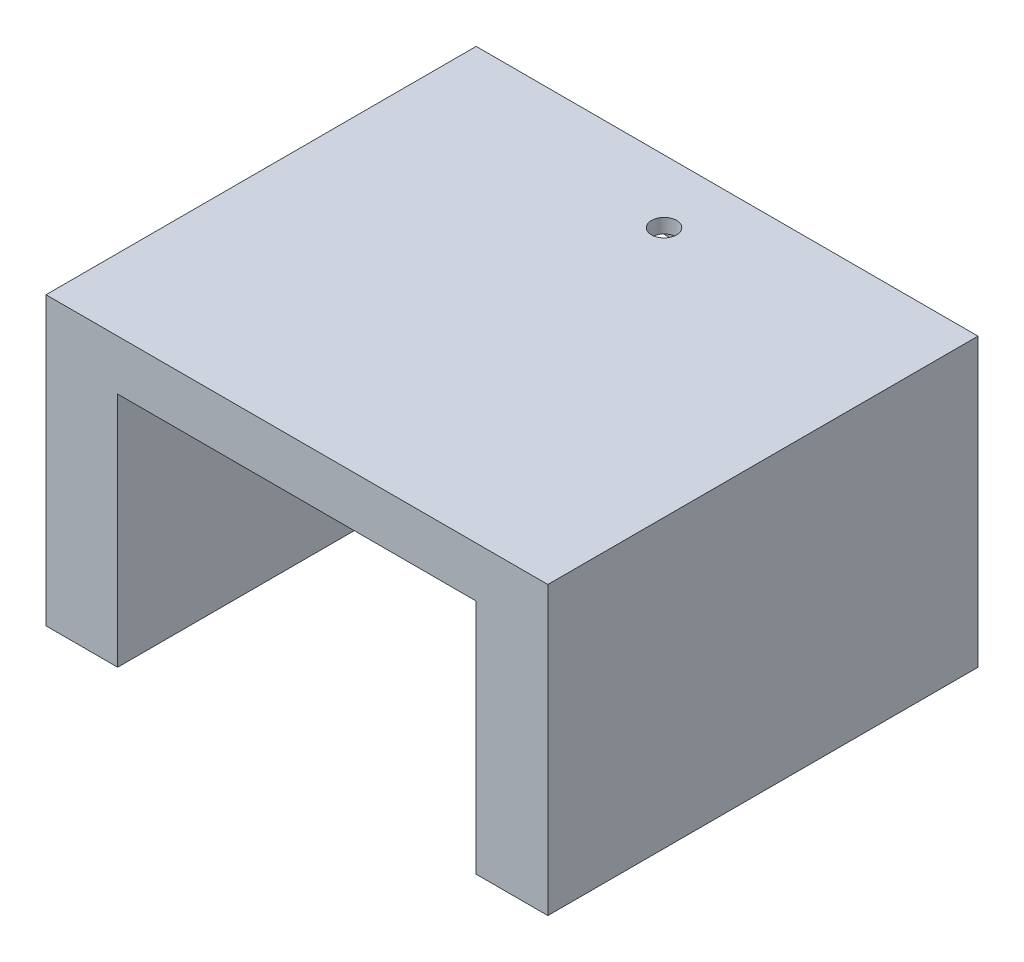
SolidWorks part; units mm, degrees
ref_plane "Front Plane" through (0, 0, 0) normal (0, 0, 1) x (1, 0, 0)
ref_plane "Top Plane" through (0, 0, 0) normal (0, 1, 0) x (1, 0, 0)
ref_plane "Right Plane" through (0, 0, 0) normal (1, 0, 0) x (0, 0, -1)
sketch "Sketch1" plane through (0, 0, 0) normal (0, 0, 1) x (1, 0, 0)
  line L2 (-59.1129, -8.3228) -> (-59.1129, -48.3228)
  line L4 (10.8871, -8.3228) -> (10.8871, -48.3228)
  line L10 (-49.1129, -15.3228) -> (-49.1129, -48.3228)
  line L11 (-49.1129, -15.3228) -> (0.8871, -15.3228)
  line L12 (0.8871, -15.3228) -> (0.8871, -48.3228)
  line L13 (-49.1129, -48.3228) -> (-59.1129, -48.3228)
  line L15 (10.8871, -8.3228) -> (-59.1129, -8.3228)
  line L16 (0.8871, -48.3228) -> (10.8871, -48.3228)
  point P4 (-54.1129, -48.3228)
  dimension "D1" = 70
  dimension "D2" = 40
  dimension "D3" = 10
  dimension "D4" = 10
  dimension "D5" = 7
  dimension "D6" = 40
extrude "Boss-Extrude1" add sketch "Sketch1" along normal blind 60
sketch "Sketch2" plane through (0, -15.3228, 0) normal (0, 1, 0) x (1, 0, 0)
  line L0 (-24.1129, 0) -> (-24.1129, -60) construction
  line L1 (-49.1129, 0) -> (0.8871, 0) construction
  line L2 (-24.1129, -60) -> (-33.849, -51.7842) construction
  line L3 (10.8871, -60) -> (-59.1129, -60) construction
  circle A0 centre (-24.1129, -8.7928) radius 1.75
  dimension "D1" = 3.5
extrude "Cut-Extrude1" cut sketch "Sketch2" against normal through all both and the other way through all from surface at 0 starting at face at (-24.1129, -15.3228, 30)
sketch "Sketch3" plane through (0, -15.3228, 0) normal (0, -1, 0) x (-1, 0, 0)
  line L0 (24.1129, 0) -> (24.1129, -14.99) construction
  line L5 (22.3629, -8.7928) -> (31.5025, -8.7928) construction
  line L7 (31.5025, -2.5956) -> (16.7232, -2.5956)
  line L8 (31.5025, -2.5956) -> (31.5025, -14.99)
  line L9 (31.5025, -14.99) -> (16.7232, -14.99)
  line L10 (16.7232, -2.5956) -> (16.7232, -14.99)
  line L11 (49.1129, 0) -> (-0.8871, 0) construction
  circle A0 centre (24.1129, -8.7928) radius 1.75 construction
  point P20 (24.1129, 0)
  dimension "D1" = 12.3944
  dimension "D2" = 14.7793
extrude "Cut-Extrude2" cut sketch "Sketch3" against normal blind 5
